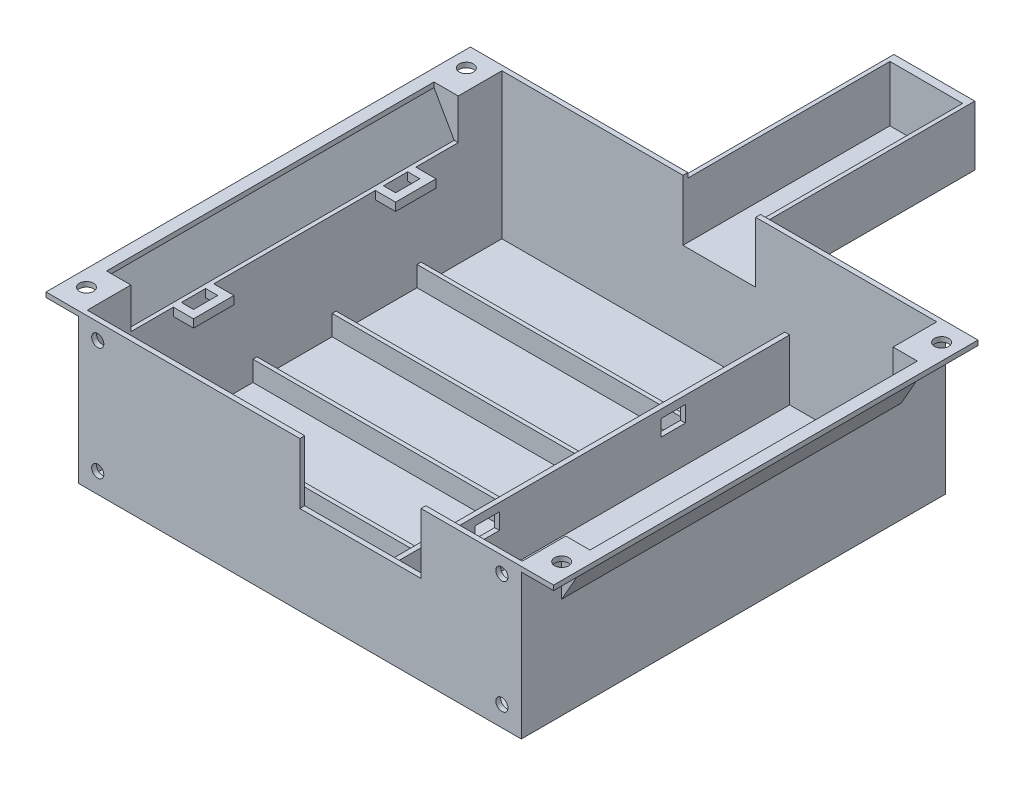
SolidWorks part; units mm, degrees
ref_plane "前视基准面" through (0, 0, 0) normal (0, 0, 1) x (1, 0, 0)
ref_plane "上视基准面" through (0, 0, 0) normal (0, 1, 0) x (1, 0, 0)
ref_plane "右视基准面" through (0, 0, 0) normal (1, 0, 0) x (0, 0, -1)
sketch "草图1" plane through (0, 0, 0) normal (0, 0, 1) x (1, 0, 0)
  line L0 (0, 0) -> (0, 21.54) construction
  line L1 (-54.8, 0) -> (54.8, 0)
  line L2 (54.8, 0) -> (54.8, 35.8)
  line L3 (54.8, 35.8) -> (62.8, 35.8)
  line L4 (62.8, 35.8) -> (62.8, 37)
  line L5 (62.8, 37) -> (53.8, 37)
  line L6 (53.8, 37) -> (53.8, 1)
  line L7 (53.8, 1) -> (17.4, 1)
  line L8 (-53.8, 37) -> (-53.8, 1)
  line L9 (-62.8, 37) -> (-53.8, 37)
  line L10 (-62.8, 35.8) -> (-62.8, 37)
  line L11 (-54.8, 35.8) -> (-62.8, 35.8)
  line L12 (-54.8, 0) -> (-54.8, 35.8)
  line L13 (16.2, 1) -> (-53.8, 1)
  line L15 (16.2, 1) -> (16.2, 16)
  line L16 (16.2, 16) -> (17.4, 16)
  line L17 (17.4, 1) -> (17.4, 16)
  point P11 (0, 1)
  dimension "D1" = 1
  dimension "D2" = 1
  dimension "D3" = 1.2
  dimension "D4" = 8
  dimension "D5" = 125.6
  dimension "D6" = 36
  dimension "D7" = 1.2
  dimension "D8" = 70
  dimension "D9" = 15
extrude "凸台-拉伸1" add sketch "草图1" along normal blind 105
sketch "草图3" plane through (0, 1, 0) normal (0, 1, 0) x (1, 0, 0)
  line L0 (53.8, -105) -> (53.8, 0) construction
  line L1 (-53.8, 0) -> (53.8, 0)
  line L2 (-53.8, 0) -> (-53.8, -1.2)
  line L3 (-53.8, -1.2) -> (53.8, -1.2)
  line L4 (53.8, 0) -> (53.8, -1.2)
  line L5 (-53.8, -105) -> (-53.8, 0) construction
  line L6 (53.8, -105) -> (-53.8, -105)
  line L7 (53.8, -105) -> (53.8, -103.8)
  line L8 (53.8, -103.8) -> (-53.8, -103.8)
  line L9 (-53.8, -105) -> (-53.8, -103.8)
  dimension "D1" = 1.2
  dimension "D2" = 1.2
extrude "凸台-拉伸3" add sketch "草图3" along normal blind 36
sketch "草图4" plane through (0, 1, 0) normal (0, 1, 0) x (1, 0, 0)
  line L0 (-53.8, -103.8) -> (-53.8, -1.2) construction
  line L1 (-53.8, -21.2) -> (16.2, -21.2)
  line L2 (-53.8, -21.2) -> (-53.8, -22.2)
  line L3 (-53.8, -22.2) -> (16.2, -22.2)
  line L4 (16.2, -21.2) -> (16.2, -22.2)
  line L5 (16.2, -103.8) -> (16.2, -1.2) construction
  line L6 (16.2, -52.5) -> (-86.0321, -52.5) construction
  line L7 (16.2, -103.8) -> (16.2, -1.2) construction
  line L8 (-53.8, -42.2) -> (16.2, -42.2)
  line L9 (-53.8, -42.2) -> (-53.8, -43.2)
  line L10 (-53.8, -43.2) -> (16.2, -43.2)
  line L11 (16.2, -42.2) -> (16.2, -43.2)
  line L12 (-53.8, -1.2) -> (16.2, -1.2) construction
  line L13 (16.2, -62.8) -> (16.2, -61.8)
  line L14 (-53.8, -61.8) -> (16.2, -61.8)
  line L15 (-53.8, -62.8) -> (-53.8, -61.8)
  line L16 (-53.8, -62.8) -> (16.2, -62.8)
  line L17 (16.2, -83.8) -> (16.2, -82.8)
  line L18 (-53.8, -82.8) -> (16.2, -82.8)
  line L19 (-53.8, -83.8) -> (-53.8, -82.8)
  line L20 (-53.8, -83.8) -> (16.2, -83.8)
  line L21 (-33.4093, -89) -> (45.3937, -89) construction
  line L22 (62.8, -105) -> (-62.8, -105) construction
  line L23 (0, -105) -> (0, 0) construction
  circle A0 centre (20, -89) radius 3
  circle A1 centre (-20, -89) radius 3
  dimension "D5" = 40
  dimension "D6" = 16
  dimension "D7" = 6
  dimension "D8" = 6
  dimension "D1" = 1
  dimension "D2" = 1
  dimension "D3" = 20
  dimension "D4" = 20
  dimension "D9" = 20
extrude "凸台-拉伸4" add sketch "草图4" along normal blind 5
sketch "草图5" plane through (0, 6, 0) normal (0, 1, 0) x (1, 0, 0)
  circle A0 centre (20, -89) radius 1.5
  circle A1 centre (-20, -89) radius 1.5
  dimension "D1" = 3
  dimension "D2" = 3
extrude "切除-拉伸1" cut sketch "草图5" against normal up to next from offset 1 offset against normal yes
sketch "草图6" plane through (0, 37, 0) normal (0, 1, 0) x (1, 0, 0)
  line L0 (0, 0) -> (0, -113.5358) construction
  line L1 (58.8, -5) -> (58.8, -114.5286) construction
  line L2 (62.8, 0) -> (-62.8, 0) construction
  line L4 (62.8, -105) -> (62.8, 0) construction
  line L5 (-53.8, -12) -> (-59.8, -12)
  line L6 (53.8, -12) -> (59.8, -12)
  line L7 (53.8, -12) -> (53.8, -93)
  line L8 (53.8, -93) -> (59.8, -93)
  line L9 (59.8, -12) -> (59.8, -93)
  line L10 (-53.8, -12) -> (-53.8, -93)
  line L11 (-53.8, -93) -> (-59.8, -93)
  line L12 (-59.8, -12) -> (-59.8, -93)
  line L13 (53.8, -103.8) -> (53.8, -1.2) construction
  circle A0 centre (58.8, -5) radius 1.75
  circle A1 centre (58.8, -99) radius 1.75
  circle A2 centre (-58.8, -99) radius 1.75
  circle A3 centre (-58.8, -5) radius 1.75
  dimension "D1" = 3.5
  dimension "D2" = 3.5
  dimension "D3" = 5
  dimension "D4" = 94
  dimension "D5" = 4
  dimension "D6" = 6
  dimension "D7" = 12
  dimension "D8" = 6
extrude "切除-拉伸2" cut sketch "草图6" against normal blind 10
sketch "草图7" plane through (0, 0, 12) normal (0, 0, 1) x (1, 0, 0)
  line L0 (60.9501, 35.8) -> (54.8, 24.9757)
  line L2 (54.8, 27) -> (59.8, 35.8)
  line L3 (59.8, 35.8) -> (60.9501, 35.8)
  line L6 (0, 0) -> (0, 41.5186) construction
  line L7 (-54.8, 0) -> (54.8, 0) construction
  line L13 (54.8, 24.9757) -> (54.8, 27)
  line L19 (54.8, 35.8) -> (54.8, 27) construction
  line L21 (59.8, 35.8) -> (54.8, 35.8) construction
  line L22 (59.8, 35.8) -> (59.8, 37) construction
  line L23 (-54.8, 24.9757) -> (-54.8, 27)
  line L24 (-59.8, 35.8) -> (-60.9501, 35.8)
  line L25 (-54.8, 27) -> (-59.8, 35.8)
  line L26 (-60.9501, 35.8) -> (-54.8, 24.9757)
  point P10 (0, 0)
  point P11 (54.8, 27)
  point P14 (53.8, 27)
  point P15 (0, 0)
  point P16 (54.8, 28)
  point P17 (0, 0)
  point P21 (0, 0)
  point P22 (59.8, 36.7988)
  point P23 (58.9976, 36)
  point P27 (59.8, 36)
  point P30 (0, 0)
  point P31 (54.8, 27)
  dimension "D1" = 1
extrude "凸台-拉伸8" add sketch "草图7" along normal blind 82
sketch "草图8" plane through (0, 0, 12) normal (0, 0, -1) x (-1, 0, 0)
  line L0 (-54.8, 35.8) -> (-60.9501, 35.8)
  line L1 (-60.9501, 35.8) -> (-54.8, 24.9757)
  line L2 (-54.8, 24.9757) -> (-54.8, 35.8)
  line L3 (0, 0) -> (0, 39.1347) construction
  line L4 (54.8, 24.9757) -> (54.8, 35.8)
  line L5 (60.9501, 35.8) -> (54.8, 24.9757)
  line L6 (54.8, 35.8) -> (60.9501, 35.8)
extrude "凸台-拉伸9" add sketch "草图8" along normal blind 1
sketch "草图10" plane through (0, 0, 94) normal (0, 0, 1) x (1, 0, 0)
  line L0 (-60.9501, 35.8) -> (-54.8, 35.8)
  line L1 (-62.8, 35.8) -> (-54.8, 35.8) construction
  line L2 (-54.8, 35.8) -> (-54.8, 24.9757)
  line L3 (-54.8, 24.9757) -> (-60.9501, 35.8)
  line L4 (0, 0) -> (0, 42.8172) construction
  line L5 (-54.8, 0) -> (54.8, 0) construction
  line L6 (54.8, 24.9757) -> (60.9501, 35.8)
  line L7 (54.8, 35.8) -> (54.8, 24.9757)
  line L8 (60.9501, 35.8) -> (54.8, 35.8)
extrude "凸台-拉伸10" add sketch "草图10" along normal blind 1
sketch "草图11" plane through (0, 0, 1.2) normal (0, 0, 1) x (1, 0, 0)
  line L0 (0, 0) -> (0, 55.8042) construction
  line L1 (-9, 37) -> (9, 37)
  line L2 (-53.8, 37) -> (53.8, 37) construction
  line L3 (9, 37) -> (9, 22)
  line L4 (9, 22) -> (-9, 22)
  line L5 (-9, 37) -> (-9, 22)
  point P10 (0, 22)
  point P11 (0, 37)
  dimension "D1" = 18
  dimension "D2" = 15
extrude "切除-拉伸3" cut sketch "草图11" against normal up to next
sketch "草图12" plane through (0, 0, 105) normal (0, 0, 1) x (1, 0, 0)
  line L0 (62.8, 37) -> (-62.8, 37) construction
  line L1 (0, 37) -> (30, 37)
  line L2 (0, 37) -> (0, 22)
  line L3 (0, 22) -> (30, 22)
  line L4 (30, 37) -> (30, 22)
  line L5 (0, 0) -> (0, 10.8054) construction
  line L6 (-54.8, 0) -> (54.8, 0) construction
  line L7 (50, 5) -> (50, 45.038) construction
  circle A0 centre (50, 5) radius 1.5
  circle A1 centre (50, 33) radius 1.5
  circle A2 centre (-50, 33) radius 1.5
  circle A3 centre (-50, 5) radius 1.5
  dimension "D3" = 3
  dimension "D4" = 3
  dimension "D5" = 28
  dimension "D6" = 5
  dimension "D7" = 100
  dimension "D1" = 30
  dimension "D2" = 15
extrude "切除-拉伸4" cut sketch "草图12" against normal up to next
sketch "草图13" plane through (0, 0, 0) normal (0, 0, -1) x (-1, 0, 0)
  line L0 (9, 35.8) -> (9, 22)
  line L1 (9, 22) -> (-9, 22)
  line L2 (-9, 22) -> (-9, 37) construction
  line L3 (9, 22) -> (-9, 22) construction
  line L4 (-9, 22) -> (-9, 35.8)
  line L5 (-9, 35.8) -> (-10, 35.8)
  line L7 (-10, 35.8) -> (-10, 21)
  line L8 (-10, 21) -> (10, 21)
  line L9 (10, 21) -> (10, 35.8)
  line L11 (10, 35.8) -> (9, 35.8)
  line L12 (9, 37) -> (62.8, 37) construction
  point P10 (0, 0)
  point P20 (9, 36.8752)
  dimension "D1" = 1
  dimension "D2" = 1
  dimension "D3" = 1
  dimension "D4" = 1.2
extrude "凸台-拉伸11" add sketch "草图13" along normal blind 50
sketch "草图14" plane through (0, 0, -50) normal (0, 0, -1) x (-1, 0, 0)
  line L1 (-10, 35.8) -> (10, 35.8)
  line L2 (-10, 35.8) -> (-10, 21)
  line L3 (-10, 21) -> (10, 21)
  line L4 (10, 35.8) -> (10, 21)
extrude "凸台-拉伸12" add sketch "草图14" along normal blind 2
sketch "草图15" plane through (0, 27, 0) normal (0, 1, 0) x (1, 0, 0)
  line L0 (-53.8, -93) -> (-53.8, -12) construction
  line L1 (-53.8, -24.5) -> (-50.8, -24.5)
  line L2 (-53.8, -24.5) -> (-53.8, -30.5)
  line L3 (-53.8, -30.5) -> (-50.8, -30.5)
  line L4 (-50.8, -24.5) -> (-50.8, -30.5)
  line L5 (-53.8, -52.5) -> (33.8394, -52.5) construction
  line L6 (-53.8, -61.8) -> (-53.8, -43.2) construction
  line L7 (-48.8, -22.5) -> (-48.8, -32.5)
  line L8 (-54.8, -32.5) -> (-48.8, -32.5)
  line L10 (-54.8, -22.5) -> (-48.8, -22.5)
  line L19 (-55.8, -22.5) -> (-55.8, -32.5) construction
  line L21 (-54.8, -93) -> (-54.8, -12) construction
  line L22 (-54.8, -32.5) -> (-54.8, -22.5)
  line L23 (-54.8, -72.5) -> (-54.8, -82.5)
  line L24 (-55.8, -22.5) -> (-48.8, -22.5) construction
  line L25 (-55.8, -32.5) -> (-48.8, -32.5) construction
  line L26 (-54.8, -82.5) -> (-48.8, -82.5)
  line L27 (-54.8, -72.5) -> (-48.8, -72.5)
  line L28 (-48.8, -82.5) -> (-48.8, -72.5)
  line L29 (-50.8, -80.5) -> (-50.8, -74.5)
  line L30 (-53.8, -74.5) -> (-50.8, -74.5)
  line L31 (-53.8, -80.5) -> (-53.8, -74.5)
  line L32 (-53.8, -80.5) -> (-50.8, -80.5)
  dimension "D2" = 6
  dimension "D3" = 3
  dimension "D4" = 40
  dimension "D1" = 2
extrude "凸台-拉伸13" add sketch "草图15" against normal blind 2
sketch "草图16" plane through (17.4, 0, 0) normal (1, 0, 0) x (0, 0, -1)
  line L0 (-53, 24.9757) -> (-53, -7.6601) construction
  line L1 (-95, 24.9757) -> (-11, 24.9757) construction
  line L2 (-73, 14) -> (-73, 10)
  line L3 (-27, 14) -> (-33, 14)
  line L4 (-27, 14) -> (-27, 10)
  line L5 (-27, 10) -> (-33, 10)
  line L6 (-33, 14) -> (-33, 10)
  line L7 (-79, 10) -> (-73, 10)
  line L8 (-79, 14) -> (-79, 10)
  line L9 (-79, 14) -> (-73, 14)
  line L10 (-103.8, 16) -> (-1.2, 16) construction
  dimension "D1" = 4
  dimension "D2" = 6
  dimension "D3" = 20
  dimension "D4" = 2
extrude "切除-拉伸5" cut sketch "草图16" against normal up to next
